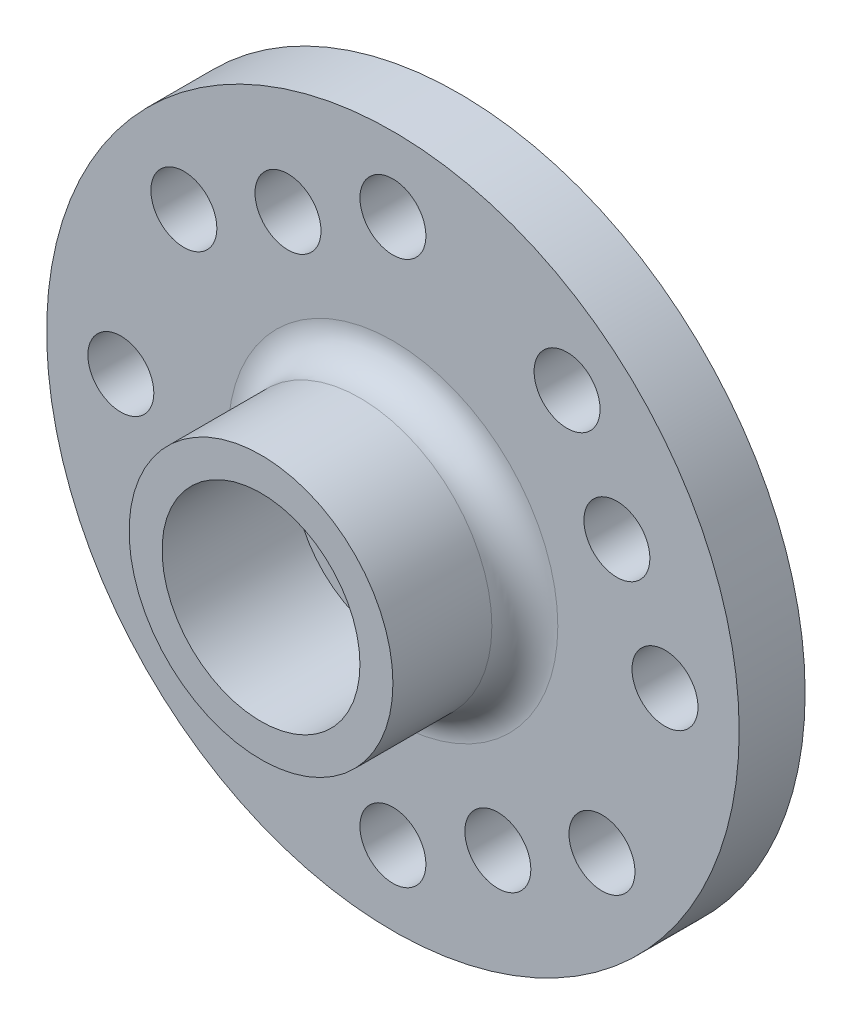
SolidWorks part; units mm, degrees
ref_plane "前基準面" through (0, 0, 0) normal (0, 0, 1) x (1, 0, 0)
ref_plane "上基準面" through (0, 0, 0) normal (0, 1, 0) x (1, 0, 0)
ref_plane "右基準面" through (0, 0, 0) normal (1, 0, 0) x (0, 0, -1)
sketch "草圖1" plane through (0, 0, 0) normal (0, 0, 1) x (1, 0, 0)
  circle A0 centre (0, 0) radius 10.5
  dimension "D1" = 21
extrude "伸長1" add sketch "草圖1" along normal blind 2
sketch "草圖2" plane through (0, 0, 2) normal (0, 0, 1) x (1, 0, 0)
  circle A0 centre (0, 0) radius 4
  circle A1 centre (0, 0) radius 3
  dimension "D1" = 6
  dimension "D2" = 8
extrude "伸長2" add sketch "草圖2" along normal blind 4
sketch "草圖5" plane through (0, 0, 2) normal (0, 0, 1) x (1, 0, 0)
  circle A0 centre (0, 0) radius 1.5
  dimension "D1" = 3
extrude "除料-伸長2" cut sketch "草圖5" against normal through all
fillet "圓角1" radius 1 1 edges at (4, 0, 2)
sketch "草圖6" plane through (0, 0, 0) normal (0, 0, -1) x (-1, 0, 0)
  circle A0 centre (0, 0) radius 3.5
  dimension "D1" = 7
extrude "伸長3" add sketch "草圖6" along normal blind 0.5
sketch "草圖8" plane through (0, 0, -0.5) normal (0, 0, -1) x (-1, 0, 0)
  circle A0 centre (0, 0) radius 3
  dimension "D1" = 6
extrude "除料-伸長3" cut sketch "草圖8" against normal blind 1.5
sketch "草圖9" plane through (0, 0, 0) normal (0, 0, -1) x (-1, 0, 0)
  line L0 (0, 0) -> (10.6295, -4.9798) construction
  line L1 (8.25, 0) -> (5.2803, -6.3388) construction
  circle A0 centre (0, 0) radius 8.25
  circle A1 centre (8.25, 0) radius 1
  circle A2 centre (0, -8.25) radius 1
  circle A3 centre (-8.25, 0) radius 1
  circle A4 centre (0, 8.25) radius 1
  circle A5 centre (5.2803, -6.3388) radius 1
  circle A6 centre (-6.3388, -5.2803) radius 1
  circle A7 centre (-5.2803, 6.3388) radius 1
  circle A8 centre (6.3388, 5.2803) radius 1
  circle A9 centre (6.7916, -3.1818) radius 1
  circle A10 centre (-3.1818, -6.7916) radius 1
  circle A11 centre (-6.7916, 3.1818) radius 1
  circle A12 centre (3.1818, 6.7916) radius 1
  dimension "D1" = 16.5
  dimension "D2" = 2
  dimension "D3" = 2
  dimension "D5" = 2
  dimension "D6" = 7.5
  dimension "D4" = 7
  dimension "D7" = 3.5
extrude "除料-伸長5" cut sketch "草圖9" against normal through all contours A4 | A3 | A2 | A5 | A9 | A1 | A8 | A12 | A7 | A11 | A6 | A10
